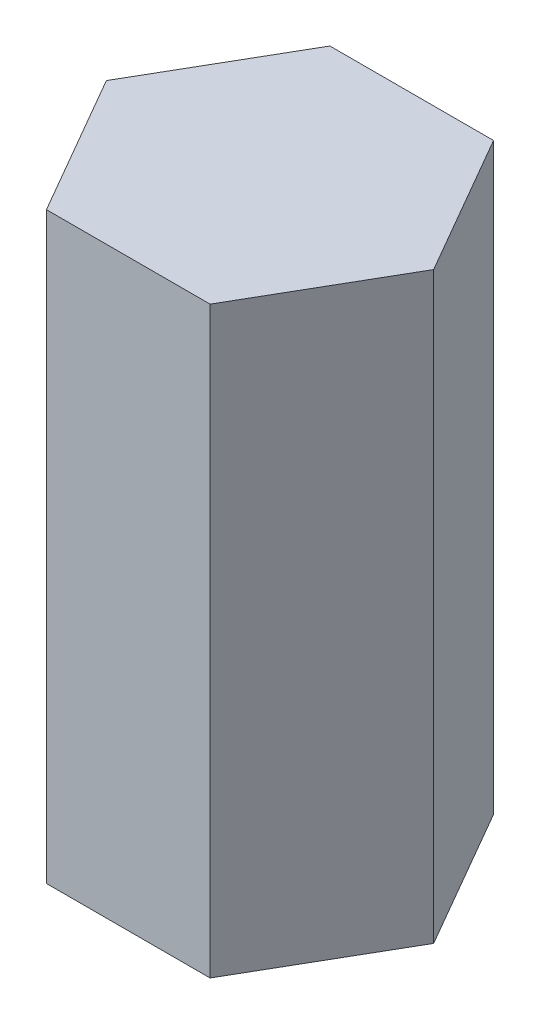
SolidWorks part; units mm, degrees
ref_plane "Płaszczyzna przednia" through (0, 0, 0) normal (0, 0, 1) x (1, 0, 0)
ref_plane "Płaszczyzna górna" through (0, 0, 0) normal (0, 1, 0) x (1, 0, 0)
ref_plane "Płaszczyzna prawa" through (0, 0, 0) normal (1, 0, 0) x (0, 0, -1)
sketch "Szkic1" plane through (0, 0, 0) normal (0, 1, 0) x (1, 0, 0)
  line L1 (9.815, 0) -> (4.9075, 8.5)
  line L2 (4.9075, 8.5) -> (-4.9075, 8.5)
  line L3 (-4.9075, 8.5) -> (-9.815, 0)
  line L4 (-9.815, 0) -> (-4.9075, -8.5)
  line L5 (-4.9075, -8.5) -> (4.9075, -8.5)
  line L6 (4.9075, -8.5) -> (9.815, 0)
  circle A0 centre (0, 0) radius 8.5
  circle A1 centre (0, 0) radius 8.5 construction
  dimension "D1" = 17
  dimension "D2" = 8.5
extrude "Dodanie-wyciągnięcie1" add sketch "Szkic1" along normal blind 35 contours A0 L4 L5 | A0 | A0 L5 L6
